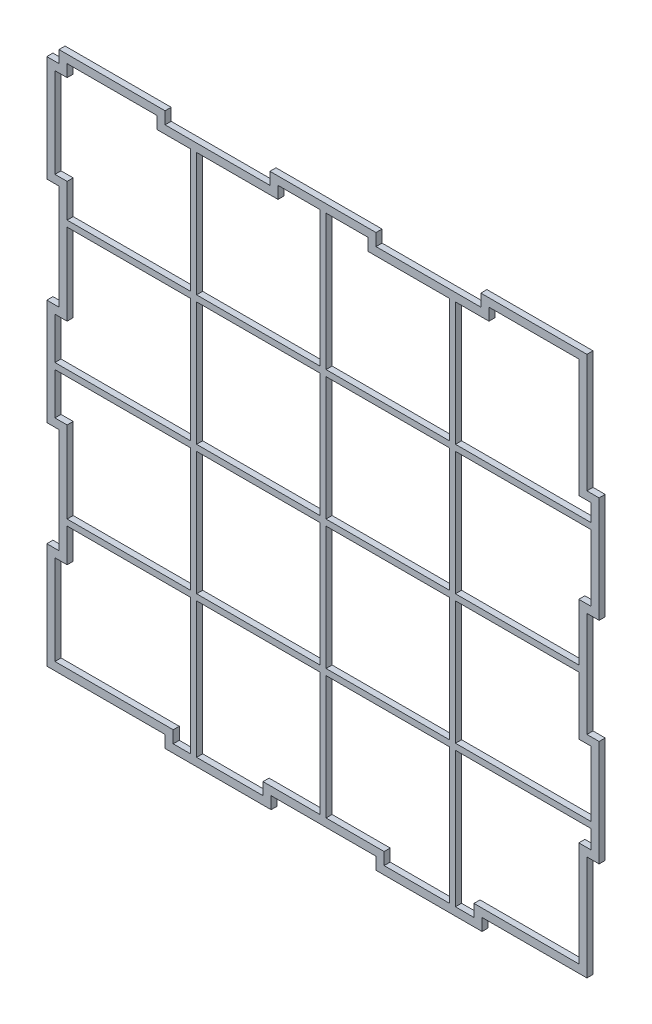
SolidWorks part; units mm, degrees
ref_plane "Front Plane" through (0, 0, 0) normal (0, 0, 1) x (1, 0, 0)
ref_plane "Top Plane" through (0, 0, 0) normal (0, 1, 0) x (1, 0, 0)
ref_plane "Right Plane" through (0, 0, 0) normal (1, 0, 0) x (0, 0, -1)
sketch "Sketch1" plane through (0, 0, 0) normal (0, 0, 1) x (1, 0, 0)
  line L0 (0, 44.4) -> (0, 65) construction
  line L1 (-44.4, 0) -> (-65, 0) construction
  line L2 (0, -44.4) -> (0, -65) construction
  line L3 (27.5446, -44.4) -> (-27.5446, -44.4) construction
  line L4 (44.4, -27.5446) -> (44.4, 27.5446) construction
  line L5 (27.5446, 44.4) -> (-27.5446, 44.4) construction
  line L6 (-44.4, -27.5446) -> (-44.4, 27.5446) construction
  line L7 (44.4, -44.4) -> (-44.4, 44.4) construction
  line L8 (44.4, 44.4) -> (-44.4, -44.4) construction
  line L14 (65, 38.88) -> (68, 38.88)
  line L18 (-65, -38.88) -> (-65, -13.06)
  line L19 (68, 38.88) -> (68, 12.76)
  line L20 (68, 12.76) -> (65, 12.76)
  line L21 (44.4, 0) -> (65, 0) construction
  line L22 (-13.06, 65) -> (-38.88, 65)
  line L26 (-38.88, 65) -> (-38.88, 68)
  line L28 (-13.06, 65) -> (-13.06, 68)
  line L29 (-13.06, 68) -> (13.06, 68)
  line L30 (13.06, 65) -> (13.06, 68)
  line L32 (38.88, 65) -> (38.88, 68)
  line L33 (38.88, 68) -> (65, 68)
  line L43 (38.88, 65) -> (13.06, 65)
  line L45 (-65, 66.5) -> (-39.18, 66.5) construction
  line L46 (-39.18, 66.5) -> (-38.88, 66.5) construction
  line L73 (-65, 38.88) -> (-68, 38.88)
  line L75 (-65, 13.06) -> (-68, 13.06)
  line L77 (-65, -13.06) -> (-68, -13.06)
  line L78 (-68, 13.06) -> (-68, -13.06)
  line L81 (-65, -38.88) -> (-68, -38.88)
  line L82 (-68, -65) -> (-68, -38.88)
  line L96 (-65, 13.06) -> (-65, 38.88)
  line L99 (-38.88, -65) -> (-64.7, -65)
  line L100 (65, 12.76) -> (65, -13.06)
  line L101 (65, -13.06) -> (68, -13.06)
  line L102 (68, -13.06) -> (68, -39.18)
  line L103 (68, -39.18) -> (65, -39.18)
  line L104 (65, -39.18) -> (65, -65)
  line L105 (65, -65) -> (39.18, -65)
  line L106 (39.18, -65) -> (39.18, -68)
  line L107 (39.18, -68) -> (13.06, -68)
  line L108 (13.06, -68) -> (13.06, -65)
  line L109 (13.06, -65) -> (-12.76, -65)
  line L110 (-12.76, -65) -> (-12.76, -68)
  line L111 (-12.76, -68) -> (-38.88, -68)
  line L112 (-38.88, -68) -> (-38.88, -65)
  line L116 (-64.7, -65) -> (-68, -65)
  line L117 (65, 68) -> (65, 64.7)
  line L118 (65, 64.7) -> (65, 38.88)
  line L119 (-38.88, 68) -> (-65, 68)
  line L120 (-65, 68) -> (-65, 65)
  line L121 (-65, 65) -> (-68, 65)
  line L122 (-68, 65) -> (-68, 38.88)
  arc A1 (-44.4, -27.5446) -> (-27.5446, -44.4) centre (0, 0) ccw construction
  arc A2 (-27.5446, 44.4) -> (-44.4, 27.5446) centre (0, 0) ccw construction
  arc A4 (44.4, 27.5446) -> (27.5446, 44.4) centre (0, 0) ccw construction
  arc A8 (27.5446, -44.4) -> (44.4, -27.5446) centre (0, 0) ccw construction
  dimension "D3" = 104.5
  dimension "D1" = 88.8
  dimension "D2" = 3
  dimension "D4" = 130
  dimension "D6" = 0.3
extrude "Boss-Extrude1" add sketch "Sketch1" along normal blind 1.5
sketch "Sketch2" plane through (0, 0, 1.5) normal (0, 0, 1) x (1, 0, 0)
  line L0 (-13.06, 65) -> (-38.88, 65) construction
  line L1 (63, -63) -> (37.18, -63)
  line L2 (63, -63) -> (63, -37.18)
  line L3 (40.88, 63) -> (11.06, 63)
  line L4 (-63, -40.88) -> (-63, -11.06)
  line L5 (63, -63) -> (-63, 63) construction
  line L6 (63, 63) -> (-63, -63) construction
  line L7 (0, 63) -> (0, 65) construction
  line L8 (-63, 0) -> (-65, 0) construction
  line L9 (-65, 38.88) -> (-65, 13.06) construction
  line L10 (-11.06, 63) -> (-11.06, 66)
  line L11 (-11.06, 66) -> (11.06, 66)
  line L12 (11.06, 66) -> (11.06, 63)
  line L13 (40.88, 63) -> (40.88, 66)
  line L14 (40.88, 66) -> (63, 66)
  line L15 (63, 66) -> (63, 63)
  line L16 (-40.88, 63) -> (-40.88, 66)
  line L17 (-40.88, 66) -> (-63, 66)
  line L18 (-63, 66) -> (-63, 63)
  line L19 (-63, 63) -> (-66, 63)
  line L20 (-66, 63) -> (-66, 40.88)
  line L21 (-66, 40.88) -> (-63, 40.88)
  line L22 (-63, 11.06) -> (-66, 11.06)
  line L23 (-66, 11.06) -> (-66, -11.06)
  line L24 (-66, -11.06) -> (-63, -11.06)
  line L25 (-63, -40.88) -> (-66, -40.88)
  line L26 (-66, -40.88) -> (-66, -63)
  line L27 (-66, -63) -> (-63, -63)
  line L28 (-36.88, -63) -> (-36.88, -66)
  line L29 (-36.88, -66) -> (-14.76, -66)
  line L30 (-14.76, -66) -> (-14.76, -63)
  line L31 (15.06, -63) -> (15.06, -66)
  line L32 (15.06, -66) -> (37.18, -66)
  line L33 (37.18, -66) -> (37.18, -63)
  line L34 (63, -37.18) -> (66, -37.18)
  line L35 (66, -37.18) -> (66, -15.06)
  line L36 (66, -15.06) -> (63, -15.06)
  line L37 (63, 14.76) -> (66, 14.76)
  line L38 (66, 14.76) -> (66, 36.88)
  line L39 (66, 36.88) -> (63, 36.88)
  line L40 (13.06, -68) -> (39.18, -68) construction
  line L41 (15.06, -66) -> (13.06, -66) construction
  line L42 (13.06, -65) -> (13.06, -68) construction
  line L43 (15.06, -66) -> (15.06, -68) construction
  line L44 (-38.88, -68) -> (-12.76, -68) construction
  line L45 (-68, 13.06) -> (-68, -13.06) construction
  line L46 (13.06, 68) -> (-13.06, 68) construction
  line L47 (68, 12.76) -> (68, 38.88) construction
  line L48 (68, -39.18) -> (68, -13.06) construction
  line L49 (-63, 11.06) -> (-63, 40.88)
  line L50 (-36.88, -63) -> (-63, -63)
  line L51 (15.06, -63) -> (-14.76, -63)
  line L52 (63, -15.06) -> (63, 14.76)
  line L53 (63, 36.88) -> (63, 63)
  line L54 (-11.06, 63) -> (-40.88, 63)
  line L55 (0.15, -65) -> (0.15, -63) construction
  line L56 (-12.76, -65) -> (13.06, -65) construction
  line L57 (63, -0.15) -> (65, -0.15) construction
  line L58 (65, -13.06) -> (65, 12.76) construction
  point P0 (0, 0)
  point P48 (26.12, -66)
  point P51 (26.12, -68)
  point P52 (-25.82, -66)
  point P55 (-66, 0)
  point P60 (0, 66)
  point P61 (66, 25.82)
  point P62 (66, -26.12)
  point P63 (-25.82, -68)
  point P64 (-68, 0)
  point P67 (0, 68)
  point P70 (68, 25.82)
  point P73 (68, -26.12)
  dimension "D1" = 2
extrude "Cut-Extrude1" cut sketch "Sketch2" against normal through all both and the other way through all
sketch "Sketch3" plane through (0, 0, 1.5) normal (0, 0, 1) x (1, 0, 0)
  line L0 (-63, 63) -> (-63, -63) construction
  line L1 (-63, 63) -> (-64.5, 63) construction
  line L2 (-63, -63) -> (-64.5, -63) construction
  line L3 (-64.5, 63) -> (-64.5, -63) construction
  line L4 (-63, -40.88) -> (-63, -11.06) construction
  line L5 (-31.125, 63) -> (-31.125, -63)
  line L6 (-31.125, 63) -> (-32.625, 63)
  line L7 (-32.625, 63) -> (-32.625, -63)
  line L8 (-31.125, -63) -> (-32.625, -63)
  line L9 (0.75, 63) -> (0.75, -63)
  line L10 (0.75, 63) -> (-0.75, 63)
  line L11 (-0.75, 63) -> (-0.75, -63)
  line L12 (0.75, -63) -> (-0.75, -63)
  line L13 (32.625, 63) -> (32.625, -63)
  line L14 (32.625, 63) -> (31.125, 63)
  line L15 (31.125, 63) -> (31.125, -63)
  line L16 (32.625, -63) -> (31.125, -63)
  line L17 (64.5, 63) -> (64.5, -63) construction
  line L18 (64.5, 63) -> (63, 63) construction
  line L19 (63, 63) -> (63, -63) construction
  line L20 (64.5, -63) -> (63, -63) construction
  line L21 (63, -37.18) -> (63, -63) construction
  line L22 (63, 63) -> (-63, 63) construction
  line L23 (63, 63) -> (63, 64.5) construction
  line L24 (-63, 63) -> (-63, 64.5) construction
  line L25 (63, 64.5) -> (-63, 64.5) construction
  line L26 (63, 31.125) -> (-63, 31.125)
  line L27 (63, 31.125) -> (63, 32.625)
  line L28 (63, 32.625) -> (-63, 32.625)
  line L29 (-63, 31.125) -> (-63, 32.625)
  line L30 (63, -0.75) -> (-63, -0.75)
  line L31 (63, -0.75) -> (63, 0.75)
  line L32 (63, 0.75) -> (-63, 0.75)
  line L33 (-63, -0.75) -> (-63, 0.75)
  line L34 (63, -32.625) -> (-63, -32.625)
  line L35 (63, -32.625) -> (63, -31.125)
  line L36 (63, -31.125) -> (-63, -31.125)
  line L37 (-63, -32.625) -> (-63, -31.125)
  line L38 (63, -64.5) -> (-63, -64.5) construction
  line L39 (63, -64.5) -> (63, -63) construction
  line L40 (63, -63) -> (-63, -63) construction
  line L41 (-63, -64.5) -> (-63, -63) construction
  line L43 (63, -63) -> (37.18, -63) construction
  line L44 (-63, 0.75) -> (-66, 0.75)
  line L45 (-66, 11.06) -> (-66, -11.06) construction
  line L46 (-66, 0.75) -> (-66, -0.75)
  line L47 (-66, -0.75) -> (-63, -0.75)
  line L48 (63, -31.125) -> (66, -31.125)
  line L49 (66, -37.18) -> (66, -15.06) construction
  line L50 (66, -31.125) -> (66, -32.625)
  line L51 (66, -32.625) -> (63, -32.625)
  line L52 (-31.125, -63) -> (-31.125, -66)
  line L53 (-36.88, -66) -> (-14.76, -66) construction
  line L54 (-31.125, -66) -> (-32.625, -66)
  line L55 (-32.625, -66) -> (-32.625, -63)
  line L56 (32.625, -63) -> (32.625, -66)
  line L57 (15.06, -66) -> (37.18, -66) construction
  line L58 (32.625, -66) -> (31.125, -66)
  line L59 (31.125, -66) -> (31.125, -63)
  line L60 (63, 32.625) -> (66, 32.625)
  line L61 (66, 14.76) -> (66, 36.88) construction
  line L62 (66, 32.625) -> (66, 31.125)
  line L63 (66, 31.125) -> (63, 31.125)
  line L64 (0.75, 63) -> (0.75, 66)
  line L65 (11.06, 66) -> (-11.06, 66) construction
  line L66 (0.75, 66) -> (-0.75, 66)
  line L67 (-0.75, 66) -> (-0.75, 63)
  line L68 (40.88, 63) -> (11.06, 63) construction
  dimension "D2" = 1.5
  dimension "D1" = 5
  dimension "D3" = 5
extrude "Boss-Extrude2" add sketch "Sketch3" against normal through all contours L66 L67 L10 L64 | L63 L62 L60 L27 | L51 L50 L48 L35 | L59 L58 L56 L16 | L55 L54 L52 L8 | L46 L47 L33 L44
